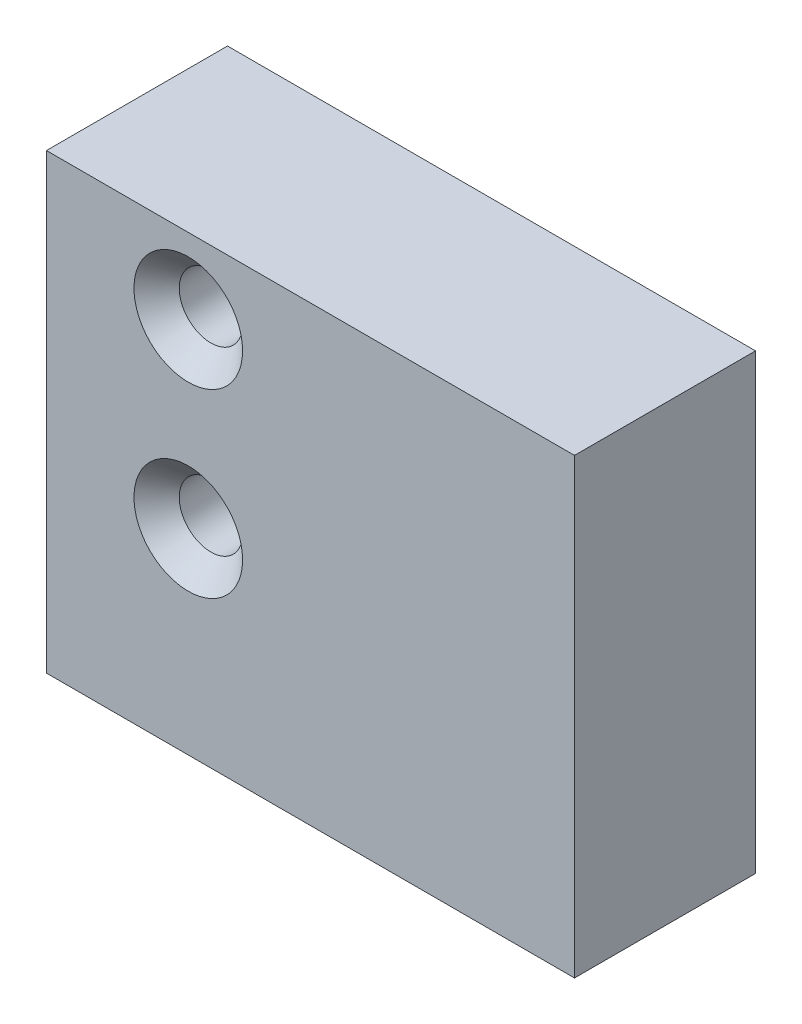
SolidWorks part; units mm, degrees
ref_plane "Plano frontal" through (0, 0, 0) normal (0, 0, 1) x (1, 0, 0)
ref_plane "Plano superior" through (0, 0, 0) normal (0, 1, 0) x (1, 0, 0)
ref_plane "Plano direito" through (0, 0, 0) normal (1, 0, 0) x (0, 0, -1)
sketch "Esboço2" plane through (0, 0, 0) normal (0, 0, 1) x (1, 0, 0)
  line L1 (101.9304, 18.163) -> (136.9304, 18.163)
  line L2 (101.9304, 18.163) -> (101.9304, -11.837)
  line L3 (101.9304, -11.837) -> (136.9304, -11.837)
  line L4 (136.9304, 18.163) -> (136.9304, -11.837)
  dimension "D1" = 30
  dimension "D2" = 35
extrude "Ressalto-extrusão1" add sketch "Esboço2" along normal blind 12
hole_wizard "Broca de rosquear para tarraxa de M5x0.82" positions "Esboço4" profile "Esboço3" hole size "M5x0.8" standard "Métrico Ansi" end condition up to next
sketch "Esboço4" plane through (0, 0, 12) normal (0, 0, 1) x (1, 0, 0)
  line L0 (101.9304, 18.163) -> (101.9304, -11.837) construction
  line L2 (86.5304, -3.837) -> (98.9304, -3.837) construction
  line L3 (136.9304, 18.163) -> (101.9304, 18.163) construction
  point P0 (111.3304, 13.163)
  point P1 (111.3304, 1.163)
  dimension "D1" = 9.4
  dimension "D2" = 9.4
  dimension "D3" = 5
  dimension "D4" = 5
sketch "Esboço3" plane through (111.3304, 13.163, 12) normal (1, 0, 0) x (0, -1, 0)
  line L0 (0, 0) -> (0, 12)
  line L1 (0, 12) -> (2.1, 12)
  line L2 (2.1, 12) -> (2.1, 0)
  line L5 (2.1, 0) -> (0, 0)
  line L11 (0, -6.35) -> (0, 107.95) construction
  dimension "Thru Hole Dia." = 4.2
  dimension "Thru Hole Depth" = 12
hole_wizard "Broca de rosquear para tarraxa de M5x0.81" positions "Esboço6" profile "Esboço5" hole size "M5x0.8" standard "Métrico Ansi"
sketch "Esboço6" plane through (0, -11.837, 0) normal (0, -1, 0) x (1, 0, 0)
  line L0 (101.9304, 12) -> (136.9304, 12) construction
  line L1 (136.9304, 12) -> (136.9304, 0) construction
  point P0 (130.9304, 6)
  point P3 (136.9304, 6)
  dimension "D1" = 6
  dimension "D2" = 6
sketch "Esboço5" plane through (130.9304, -11.837, 6) normal (1, 0, 0) x (0, 0, -1)
  line L0 (0, 0) -> (0, 21.2618)
  line L1 (0, 21.2618) -> (2.1, 20)
  line L2 (2.1, 20) -> (2.1, 0)
  line L5 (2.1, 0) -> (0, 0)
  line L10 (0, 21.2618) -> (-2.1, 20) construction
  line L11 (0, -6.35) -> (0, 107.95) construction
  dimension "Hole Dia." = 4.2
  dimension "Hole Depth" = 20
  dimension "Drill Angle" = 118
cosmetic thread "Representação de rosca1" parameters "D2"=5
chamfer "Chanfro1" distance 1.5 angle 45 2 edges at (113.4304, 1.163, 12) (113.4304, 13.163, 12)
chamfer "Chanfro2" distance 1.5 angle 45 1 edges at (113.4304, 1.163, 0)
chamfer "Chanfro3" distance 1.5 angle 45 1 edges at (113.4304, 13.163, 0)
